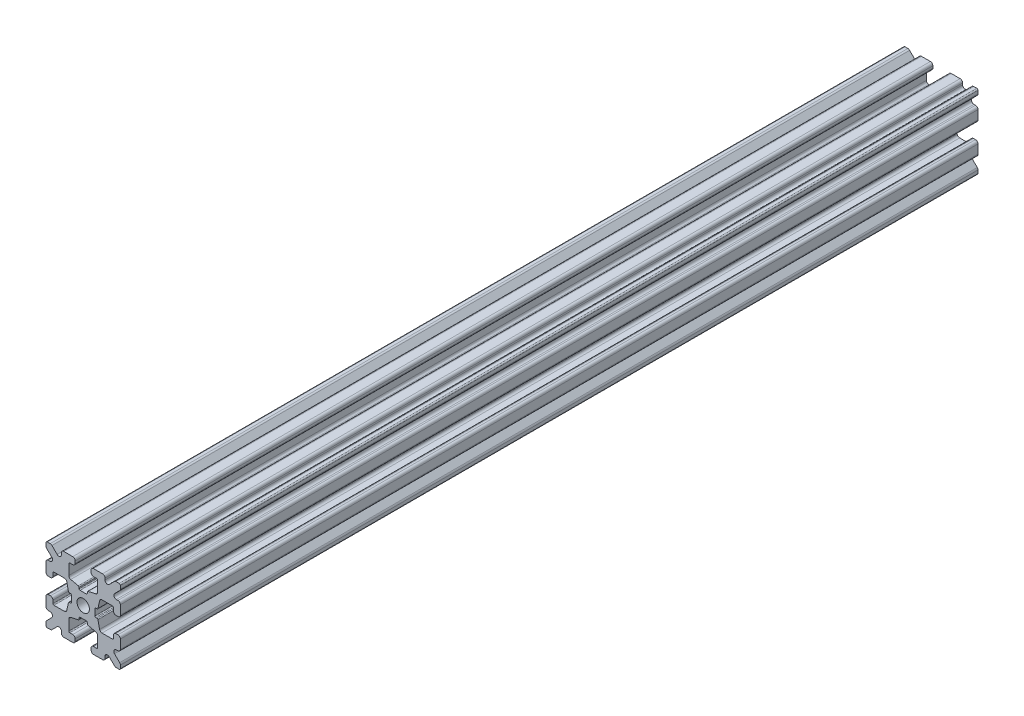
SolidWorks part; units mm, degrees
ref_plane "Front Plane" through (0, 0, 0) normal (0, 0, 1) x (1, 0, 0)
ref_plane "Top Plane" through (0, 0, 0) normal (0, 1, 0) x (1, 0, 0)
ref_plane "Right Plane" through (0, 0, 0) normal (1, 0, 0) x (0, 0, -1)
sketch "Sketch1" plane through (0, 0, 0) normal (0, 0, 1) x (1, 0, 0)
  line L1 (-7.5, -7.5) -> (7.5, -7.5)
  line L2 (-7.5, -7.5) -> (-7.5, 7.5)
  line L3 (-7.5, 7.5) -> (7.5, 7.5)
  line L4 (7.5, -7.5) -> (7.5, 7.5)
  line L5 (-7.5, -7.5) -> (7.5, 7.5) construction
  line L6 (-7.5, 7.5) -> (7.5, -7.5) construction
  circle A0 centre (0, 0) radius 1.25
  point P0 (0, 0)
  dimension "D2" = 2.5
  dimension "D1" = 15
extrude "Boss-Extrude1" add sketch "Sketch1" along normal mid plane 173
fillet "Fillet1" radius 0.25 4 edges at (7.5, -7.5, 0) (-7.5, -7.5, 0) (7.5, 7.5, 0) (-7.5, 7.5, 0)
sketch "Sketch2" plane through (0, 0, 86.5) normal (0, 0, 1) x (1, 0, 0)
  line L0 (-7.5, 7.25) -> (-7.5, -7.25) construction
  line L1 (-7.5, 1.6) -> (-6.1, 1.6)
  line L2 (-7.5, 1.6) -> (-7.5, -1.6)
  line L3 (-7.5, -1.6) -> (-6.1, -1.6)
  line L4 (-6.1, 1.6) -> (-6.1, 2.9)
  line L5 (0, 0) -> (-12.1036, 0) construction
  line L6 (-6.1, -2.9) -> (-3.4, -2.9)
  line L7 (0, 0) -> (-7.25, 7.25) construction
  line L8 (-6.1, 2.9) -> (-3.4, 2.9)
  line L9 (-3.4, -2.9) -> (-3.4, 2.9)
  line L10 (55, 0) -> (-55, 0) construction
  line L11 (-6.1, -2.9) -> (-6.1, -1.6)
  line L12 (2.9, 6.1) -> (1.6, 6.1)
  line L13 (2.9, 3.4) -> (-2.9, 3.4)
  line L14 (-2.9, 6.1) -> (-2.9, 3.4)
  line L15 (2.9, 6.1) -> (2.9, 3.4)
  line L16 (-1.6, 6.1) -> (-2.9, 6.1)
  line L17 (1.6, 7.5) -> (1.6, 6.1)
  line L18 (-1.6, 7.5) -> (1.6, 7.5)
  line L19 (-1.6, 7.5) -> (-1.6, 6.1)
  line L20 (-1.6, -7.5) -> (-1.6, -6.1)
  line L21 (-1.6, -7.5) -> (1.6, -7.5)
  line L22 (1.6, -7.5) -> (1.6, -6.1)
  line L23 (-1.6, -6.1) -> (-2.9, -6.1)
  line L24 (2.9, -6.1) -> (2.9, -3.4)
  line L25 (-2.9, -6.1) -> (-2.9, -3.4)
  line L26 (2.9, -3.4) -> (-2.9, -3.4)
  line L27 (2.9, -6.1) -> (1.6, -6.1)
  line L28 (6.1, -2.9) -> (6.1, -1.6)
  line L29 (3.4, -2.9) -> (3.4, 2.9)
  line L30 (6.1, 2.9) -> (3.4, 2.9)
  line L31 (6.1, -2.9) -> (3.4, -2.9)
  line L32 (6.1, 1.6) -> (6.1, 2.9)
  line L33 (7.5, -1.6) -> (6.1, -1.6)
  line L34 (7.5, 1.6) -> (7.5, -1.6)
  line L35 (7.5, 1.6) -> (6.1, 1.6)
  dimension "D1" = 3.2
  dimension "D2" = 5.8
  dimension "D3" = 1.4
  dimension "D4" = 2.7
extrude "Cut-Extrude1" cut sketch "Sketch2" against normal through all
sketch "Sketch4" plane through (0, 0, 86.5) normal (0, 0, 1) x (1, 0, 0)
  line L0 (-3.4, 2.9) -> (-2.75, 0)
  line L1 (55, 0) -> (-55, 0) construction
  line L2 (-2.75, 0) -> (-3.4, -2.9)
  line L3 (-3.4, -2.9) -> (-3.4, 2.9) construction
  line L4 (-3.4, 2.9) -> (-3.4, -2.9)
  line L5 (-2.9, 3.4) -> (0, 2.75)
  line L6 (0, 2.75) -> (2.9, 3.4)
  line L7 (2.9, 3.4) -> (-2.9, 3.4)
  line L8 (3.4, 2.9) -> (2.75, 0)
  line L9 (2.75, 0) -> (3.4, -2.9)
  line L10 (3.4, -2.9) -> (3.4, 2.9)
  line L11 (-2.9, -3.4) -> (0, -2.75)
  line L12 (0, -2.75) -> (2.9, -3.4)
  line L13 (2.9, -3.4) -> (-2.9, -3.4)
  circle A2 centre (0, 0) radius 2.75
  circle A3 centre (0, 0) radius 2.75 construction
  dimension "D1" = 1.5
extrude "Cut-Extrude3" cut sketch "Sketch4" against normal through all
fillet "Fillet3" radius 0.5 16 edges at (-6.1, -1.6, 0) (-7.5, -1.6, 0) (-6.1, 1.6, 0) (-7.5, 1.6, 0) (-1.6, -7.5, 0) (-1.6, -6.1, 0) (1.6, -7.5, 0) (1.6, -6.1, 0) (6.1, -1.6, 0) (7.5, -1.6, 0) (7.5, 1.6, 0) (6.1, 1.6, 0) (1.6, 7.5, 0) (1.6, 6.1, 0) (-1.6, 7.5, 0) (-1.6, 6.1, 0)
fillet "Fillet4" radius 0.5 8 edges at (-3.4, 2.9, 0) (-3.4, -2.9, 0) (2.9, -3.4, 0) (-2.9, -3.4, 0) (3.4, -2.9, 0) (3.4, 2.9, 0) (-2.9, 3.4, 0) (2.9, 3.4, 0)
fillet "Fillet5" radius 3 4 edges at (0, -2.75, 0) (2.75, 0, 0) (-2.75, 0, 0) (0, 2.75, 0)
fillet "Fillet6" radius 0.2 8 edges at (-2.9, -6.1, 0) (2.9, -6.1, 0) (6.1, -2.9, 0) (6.1, 2.9, 0) (2.9, 6.1, 0) (-2.9, 6.1, 0) (-6.1, -2.9, 0) (-6.1, 2.9, 0)
sketch "Sketch5" plane through (0, 0, 86.5) normal (0, 0, 1) x (1, 0, 0)
  line L0 (0, 0) -> (-7.25, 7.25) construction
  line L1 (-7.5, 6.4393) -> (-5.4607, 4.4)
  line L2 (-6.4393, 7.5) -> (-4.4, 5.4607)
  line L3 (-7.5, 4.4) -> (-5.4607, 4.4)
  line L4 (-3.8003, 2.9) -> (-5.9, 2.9) construction
  line L5 (0, 0) -> (-12.1819, 0) construction
  line L6 (-4.4, 7.5) -> (-4.4, 5.4607)
  line L7 (-2.9, 5.9) -> (-2.9, 3.8003) construction
  line L8 (-7.5, 6.4393) -> (-7.5, 4.4)
  line L9 (-7.5, 7.25) -> (-7.5, 2.1) construction
  line L10 (2.1, -7.5) -> (7.25, -7.5) construction
  line L11 (7.5, -7.25) -> (7.5, -2.1) construction
  line L12 (7.25, 7.5) -> (2.1, 7.5) construction
  line L13 (-2.1, 7.5) -> (-7.25, 7.5) construction
  line L14 (-4.4, 7.5) -> (-6.4393, 7.5)
  line L16 (55, 0) -> (-55, 0) construction
  line L17 (0, 0) -> (0, 10.993) construction
  line L18 (0, -54.6431) -> (0, 54.6431) construction
  line L20 (4.4, 7.5) -> (6.4393, 7.5)
  line L22 (7.5, 6.4393) -> (7.5, 4.4)
  line L23 (4.4, 7.5) -> (4.4, 5.4607)
  line L24 (7.5, 4.4) -> (5.4607, 4.4)
  line L25 (6.4393, 7.5) -> (4.4, 5.4607)
  line L26 (7.5, 6.4393) -> (5.4607, 4.4)
  line L27 (7.5, -6.4393) -> (5.4607, -4.4)
  line L28 (6.4393, -7.5) -> (4.4, -5.4607)
  line L29 (7.5, -4.4) -> (5.4607, -4.4)
  line L30 (4.4, -7.5) -> (4.4, -5.4607)
  line L31 (7.5, -6.4393) -> (7.5, -4.4)
  line L33 (4.4, -7.5) -> (6.4393, -7.5)
  line L36 (-4.4, -7.5) -> (-6.4393, -7.5)
  line L38 (-7.5, -6.4393) -> (-7.5, -4.4)
  line L39 (-4.4, -7.5) -> (-4.4, -5.4607)
  line L40 (-7.5, -4.4) -> (-5.4607, -4.4)
  line L41 (-6.4393, -7.5) -> (-4.4, -5.4607)
  line L42 (-7.5, -6.4393) -> (-5.4607, -4.4)
  dimension "D1" = 1.5
  dimension "D2" = 1.5
  dimension "D3" = 1.5
extrude "Cut-Extrude4" cut sketch "Sketch5" against normal through all
fillet "Fillet8" radius 0.5 24 edges at (-5.4607, 4.4, 0) (-7.5, 4.4, 0) (-5.4607, -4.4, 0) (-7.5, -4.4, 0) (-4.4, -7.5, 0) (-4.4, -5.4607, 0) (4.4, -7.5, 0) (4.4, -5.4607, 0) (5.4607, -4.4, 0) (7.5, -4.4, 0) (7.5, 4.4, 0) (5.4607, 4.4, 0) (4.4, 5.4607, 0) (4.4, 7.5, 0) (-4.4, 5.4607, 0) (-4.4, 7.5, 0) (-6.4393, 7.5, 0) (-7.5, 6.4393, 0) (6.4393, 7.5, 0) (7.5, 6.4393, 0) (6.4393, -7.5, 0) (7.5, -6.4393, 0) (-6.4393, -7.5, 0) (-7.5, -6.4393, 0)
sketch "Sketch6" plane through (0, 0, 86.5) normal (0, 0, 1) x (1, 0, 0)
  line L0 (0, 0) -> (0, 11.013) construction
  line L1 (0.6561, 2.8971) -> (2.1235, 2.8971) construction
  line L2 (0, -54.6431) -> (0, 54.6431) construction
  line L3 (0, 0) -> (7.25, 7.25) construction
  line L4 (7.5, 0.8255) -> (7.5, -0.8255)
  line L5 (2.3471, 0.8255) -> (7.5, 0.8255)
  line L6 (0, 0) -> (12.4016, 0) construction
  line L7 (0.8255, -7.5) -> (-0.8255, -7.5)
  line L8 (2.3471, -0.8255) -> (2.3471, 0.8255)
  line L9 (0.8255, -2.3471) -> (0.8255, -7.5)
  line L10 (7.5, -0.8255) -> (2.3471, -0.8255)
  line L11 (-7.5, -0.8255) -> (-2.3471, -0.8255)
  line L12 (-2.3471, -0.8255) -> (-2.3471, 0.8255)
  line L13 (-0.8255, -2.3471) -> (0.8255, -2.3471)
  line L14 (-0.8255, 7.5) -> (-0.8255, 2.3471)
  line L15 (-0.8255, 2.3471) -> (0.8255, 2.3471)
  line L16 (-0.8255, -7.5) -> (-0.8255, -2.3471)
  line L17 (0.8255, 2.3471) -> (0.8255, 7.5)
  line L18 (0.8255, 7.5) -> (-0.8255, 7.5)
  line L19 (3.9, 7.5) -> (2.1, 7.5) construction
  line L20 (-2.3471, 0.8255) -> (-7.5, 0.8255)
  line L21 (-7.5, 0.8255) -> (-7.5, -0.8255)
  point P5 (0, -2.5973)
  point P7 (0, 2.5973)
  dimension "D3" = 0.55
  dimension "D1" = 1.651
extrude "Cut-Extrude5" cut sketch "Sketch6" against normal through all
fillet "Fillet10" radius 0.2 16 edges at (-2.935, 0.8255, 0) (-2.935, -0.8255, 0) (2.935, -0.8255, 0) (2.935, 0.8255, 0) (0.8255, 2.935, 0) (-0.8255, 2.935, 0) (-2.3471, 0.8255, 0) (-2.3471, -0.8255, 0) (0.8255, 2.3471, 0) (-0.8255, 2.3471, 0) (2.3471, 0.8255, 0) (2.3471, -0.8255, 0) (0.8255, -2.935, 0) (0.8255, -2.3471, 0) (-0.8255, -2.3471, 0) (-0.8255, -2.935, 0)
